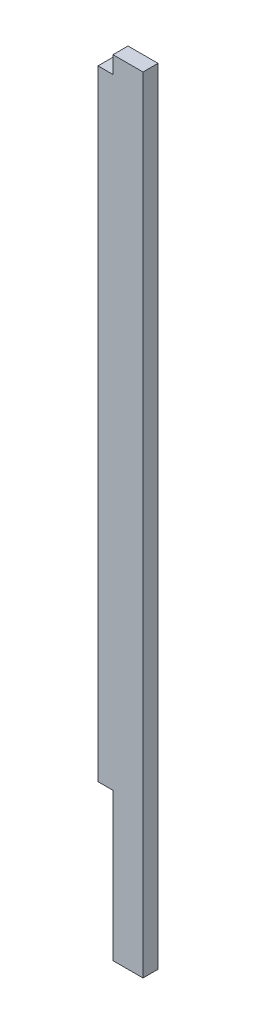
SolidWorks part; units mm, degrees
ref_plane "Front Plane" through (0, 0, 0) normal (0, 0, 1) x (1, 0, 0)
ref_plane "Top Plane" through (0, 0, 0) normal (0, 1, 0) x (1, 0, 0)
ref_plane "Right Plane" through (0, 0, 0) normal (1, 0, 0) x (0, 0, -1)
sketch "Sketch1" plane through (0, 0, 0) normal (0, 0, 1) x (1, 0, 0)
  line L1 (-8.1153, -121.158) -> (8.1153, -121.158)
  line L2 (-8.1153, -121.158) -> (-8.1153, 121.158)
  line L3 (-8.1153, 121.158) -> (8.1153, 121.158)
  line L4 (8.1153, -121.158) -> (8.1153, 121.158)
  line L5 (-8.1153, -121.158) -> (8.1153, 121.158) construction
  line L6 (-8.1153, 121.158) -> (8.1153, -121.158) construction
  line L7 (-8.1153, 121.158) -> (-2.7051, 121.158)
  line L8 (-8.1153, 121.158) -> (-8.1153, 114.9604)
  line L9 (-8.1153, 114.9604) -> (-2.7051, 114.9604)
  line L10 (-2.7051, 121.158) -> (-2.7051, 114.9604)
  line L11 (-2.7051, -121.158) -> (-2.7051, -108.6104)
  line L12 (-8.1153, -108.6104) -> (-2.7051, -108.6104)
  line L13 (-8.1153, -121.158) -> (-8.1153, -108.6104)
  line L14 (-8.1153, -121.158) -> (-2.7051, -121.158)
  point P0 (0, 0)
  dimension "D1" = 16.2306
  dimension "D2" = 242.316
  dimension "D3" = 6.1976
  dimension "D4" = 5.4102
  dimension "D5" = 12.5476
extrude "Boss-Extrude1" add sketch "Sketch1" along normal blind 5.4102 contours L2 L12 L11 L1 L4 L3 L10 L9
sketch "Sketch2" plane through (0, 0, 5.4102) normal (0, 0, 1) x (1, 0, 0)
  line L1 (-2.7051, -121.158) -> (8.1153, -121.158)
  line L2 (-2.7051, -121.158) -> (-2.7051, -161.798)
  line L3 (-2.7051, -161.798) -> (8.1153, -161.798)
  line L4 (8.1153, -121.158) -> (8.1153, -161.798)
  dimension "D1" = 40.64
extrude "Boss-Extrude2" add sketch "Sketch2" against normal blind 5.4102
